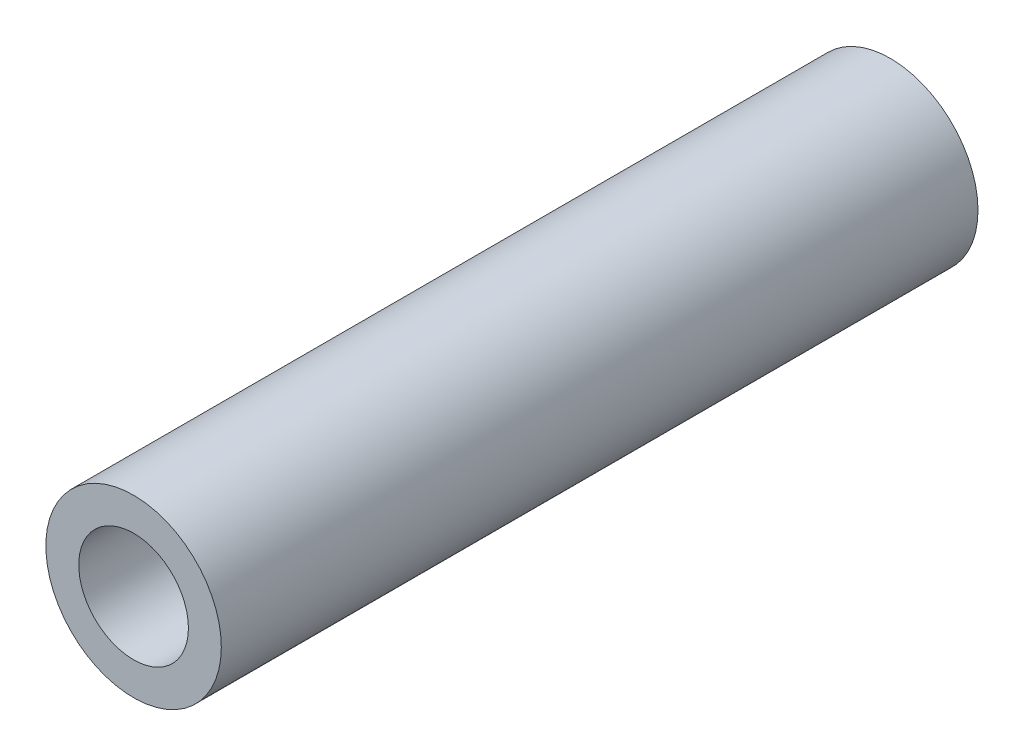
SolidWorks part; units mm, degrees
ref_plane "Front" through (0, 0, 0) normal (0, 0, 1) x (1, 0, 0)
ref_plane "Top" through (0, 0, 0) normal (0, 1, 0) x (1, 0, 0)
ref_plane "Right" through (0, 0, 0) normal (1, 0, 0) x (0, 0, -1)
sketch "Sketch1" plane through (0, 0, 0) normal (0, 0, 1) x (1, 0, 0)
  circle A0 centre (0, 0) radius 5
  circle A1 centre (0, 0) radius 8
  dimension "D1" = 10
  dimension "D2" = 16
extrude "Extrude1" add sketch "Sketch1" along normal blind 69
